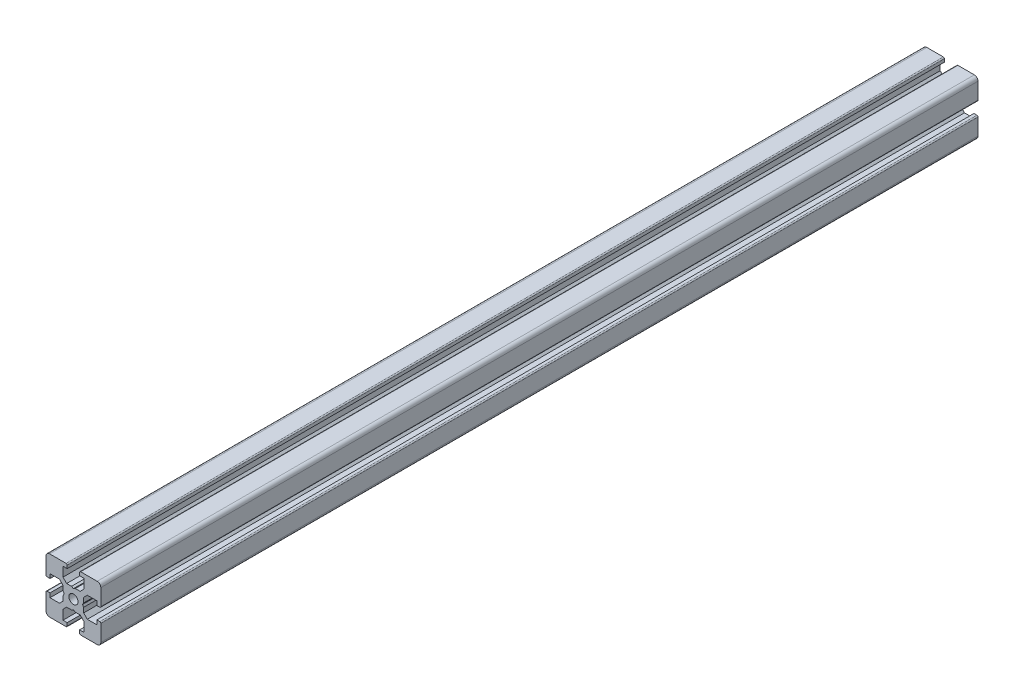
SolidWorks part; units mm, degrees
ref_plane "Front" through (0, 0, 0) normal (0, 0, 1) x (1, 0, 0)
ref_plane "Top" through (0, 0, 0) normal (0, 1, 0) x (1, 0, 0)
ref_plane "Right" through (0, 0, 0) normal (1, 0, 0) x (0, 0, -1)
ref_plane "Plane1" through (0, 0, 300) normal (0, 0, 1) x (1, 0, 0)
sketch "Sketch1" plane through (0, 0, 300) normal (0, 0, 1) x (1, 0, 0)
  line L0 (-7.5, 6.5) -> (-7.5, 2)
  line L1 (-7.2, 1.7) -> (-6.4, 1.7)
  line L2 (-6.4, 1.7) -> (-6.4, 2.85)
  line L3 (-6.4, 2.85) -> (-3.8, 2.85)
  line L4 (-3.8, 2.85) -> (-2.8, 1.85)
  line L5 (-2.8, 1.85) -> (-2.8, 0.5196)
  line L6 (-2.8, 0.5196) -> (-2.5, 0)
  line L7 (-2.5, 0) -> (-2.8, -0.5196)
  line L8 (-2.8, -0.5196) -> (-2.8, -1.85)
  line L9 (-2.8, -1.85) -> (-3.8, -2.85)
  line L10 (-3.8, -2.85) -> (-6.4, -2.85)
  line L11 (-6.4, -2.85) -> (-6.4, -1.7)
  line L12 (-6.4, -1.7) -> (-7.2, -1.7)
  line L13 (-7.5, -2) -> (-7.5, -6.5)
  line L14 (-6.5, -7.5) -> (-2, -7.5)
  line L15 (-1.7, -7.2) -> (-1.7, -6.4)
  line L16 (-1.7, -6.4) -> (-2.85, -6.4)
  line L17 (-2.85, -6.4) -> (-2.85, -3.8)
  line L18 (-2.85, -3.8) -> (-1.85, -2.8)
  line L19 (-1.85, -2.8) -> (-0.5196, -2.8)
  line L20 (-0.5196, -2.8) -> (0, -2.5)
  line L21 (0, -2.5) -> (0.5196, -2.8)
  line L22 (0.5196, -2.8) -> (1.85, -2.8)
  line L23 (1.85, -2.8) -> (2.85, -3.8)
  line L24 (2.85, -3.8) -> (2.85, -6.4)
  line L25 (2.85, -6.4) -> (1.7, -6.4)
  line L26 (1.7, -6.4) -> (1.7, -7.2)
  line L27 (2, -7.5) -> (6.5, -7.5)
  line L28 (7.5, -6.5) -> (7.5, -2)
  line L29 (7.2, -1.7) -> (6.4, -1.7)
  line L30 (6.4, -1.7) -> (6.4, -2.85)
  line L31 (6.4, -2.85) -> (3.8, -2.85)
  line L32 (3.8, -2.85) -> (2.8, -1.85)
  line L33 (2.8, -1.85) -> (2.8, -0.5196)
  line L34 (2.8, -0.5196) -> (2.5, 0)
  line L35 (2.5, 0) -> (2.8, 0.5196)
  line L36 (2.8, 0.5196) -> (2.8, 1.85)
  line L37 (2.8, 1.85) -> (3.8, 2.85)
  line L38 (3.8, 2.85) -> (6.4, 2.85)
  line L39 (6.4, 2.85) -> (6.4, 1.7)
  line L40 (6.4, 1.7) -> (7.2, 1.7)
  line L41 (7.5, 2) -> (7.5, 6.5)
  line L42 (6.5, 7.5) -> (2, 7.5)
  line L43 (1.7, 7.2) -> (1.7, 6.4)
  line L44 (1.7, 6.4) -> (2.85, 6.4)
  line L45 (2.85, 6.4) -> (2.85, 3.8)
  line L46 (2.85, 3.8) -> (1.85, 2.8)
  line L47 (1.85, 2.8) -> (0.5196, 2.8)
  line L48 (0.5196, 2.8) -> (0, 2.5)
  line L49 (0, 2.5) -> (-0.5196, 2.8)
  line L50 (-0.5196, 2.8) -> (-1.85, 2.8)
  line L51 (-1.85, 2.8) -> (-2.85, 3.8)
  line L52 (-2.85, 3.8) -> (-2.85, 6.4)
  line L53 (-2.85, 6.4) -> (-1.7, 6.4)
  line L54 (-1.7, 6.4) -> (-1.7, 7.2)
  line L55 (-2, 7.5) -> (-6.5, 7.5)
  circle A0 centre (0, 0) radius 1.25
  arc A1 (-7.5, 2) -> (-7.2, 1.7) centre (-7.2, 2) ccw
  arc A2 (-7.2, -1.7) -> (-7.5, -2) centre (-7.2, -2) ccw
  arc A3 (-7.5, -6.5) -> (-6.5, -7.5) centre (-6.5, -6.5) ccw
  arc A4 (-2, -7.5) -> (-1.7, -7.2) centre (-2, -7.2) ccw
  arc A5 (1.7, -7.2) -> (2, -7.5) centre (2, -7.2) ccw
  arc A6 (6.5, -7.5) -> (7.5, -6.5) centre (6.5, -6.5) ccw
  arc A7 (7.5, -2) -> (7.2, -1.7) centre (7.2, -2) ccw
  arc A8 (7.2, 1.7) -> (7.5, 2) centre (7.2, 2) ccw
  arc A9 (7.5, 6.5) -> (6.5, 7.5) centre (6.5, 6.5) ccw
  arc A10 (2, 7.5) -> (1.7, 7.2) centre (2, 7.2) ccw
  arc A11 (-1.7, 7.2) -> (-2, 7.5) centre (-2, 7.2) ccw
  arc A12 (-6.5, 7.5) -> (-7.5, 6.5) centre (-6.5, 6.5) ccw
extrude "Boss-Extrude1" add sketch "Sketch1" against normal blind 240
